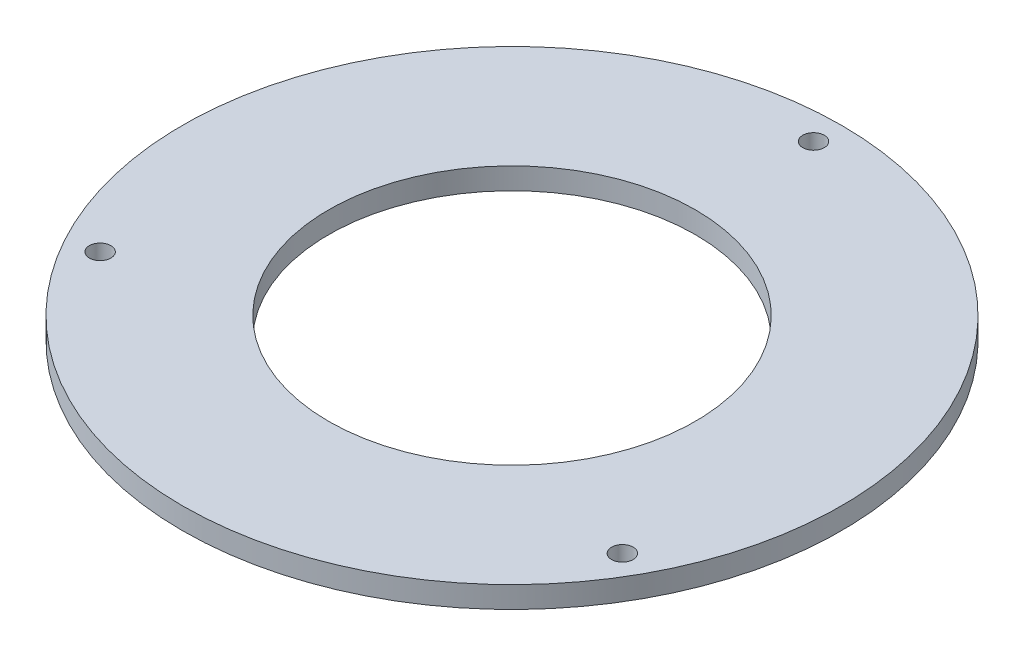
SolidWorks part; units mm, degrees
material "6061 Alloy"
ref_plane "Front Plane" through (0, 0, 0) normal (0, 0, 1) x (1, 0, 0)
ref_plane "Top Plane" through (0, 0, 0) normal (0, 1, 0) x (1, 0, 0)
ref_plane "Right Plane" through (0, 0, 0) normal (1, 0, 0) x (0, 0, -1)
sketch "Sketch1" plane through (0, 0, 0) normal (0, 1, 0) x (1, 0, 0)
  circle A0 centre (0, 0) radius 97.028
  dimension "D1" = 194.056
extrude "Boss-Extrude1" add sketch "Sketch1" along normal blind 6.35
sketch "Sketch2" plane through (0, 6.35, 0) normal (0, 1, 0) x (1, 0, 0)
  line L0 (0, 0) -> (0, 88.773) construction
  circle A0 centre (0, 88.773) radius 3.175
  circle A1 centre (76.8797, -44.3865) radius 3.175
  circle A2 centre (-76.8797, -44.3865) radius 3.175
  point P10 (0, 0)
  dimension "D2" = 6.35
  dimension "D1" = 88.773
  dimension "D3" = 3
extrude "Cut-Extrude1" cut sketch "Sketch2" against normal through all
sketch "Sketch3" plane through (0, 6.35, 0) normal (0, 1, 0) x (1, 0, 0)
  circle A0 centre (0, 0) radius 53.975
  dimension "D1" = 107.95
extrude "Cut-Extrude2" cut sketch "Sketch3" against normal through all
